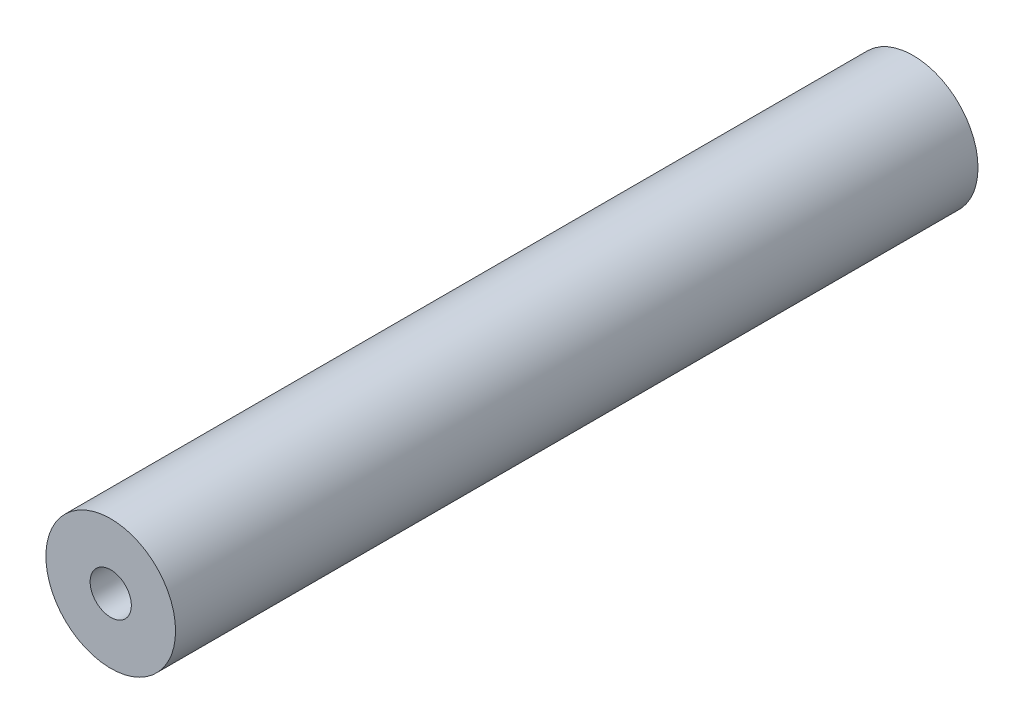
SolidWorks part; units mm, degrees
material "6061-T6 (SS)"
ref_plane "Front Plane" through (0, 0, 0) normal (0, 0, 1) x (1, 0, 0)
ref_plane "Top Plane" through (0, 0, 0) normal (0, 1, 0) x (1, 0, 0)
ref_plane "Right Plane" through (0, 0, 0) normal (1, 0, 0) x (0, 0, -1)
sketch "Sketch1" plane through (0, 0, 0) normal (0, 0, 1) x (1, 0, 0)
  circle A1 centre (0, 0) radius 6.35
  dimension "D2" = 12.7
extrude "Boss-Extrude1" add sketch "Sketch1" along normal mid plane 78.5812
hole_wizard "#10-32 Tapped Hole1" positions "3DSketch1" profile "Sketch2" tap size "#10-32" standard "ANSI Inch"
sketch3d "3DSketch1"
  line L0 (0, 0, 39.2906) -> (0, 0, -39.2906) construction
  point P0 (0, 0, -39.2906)
  point P4 (0, 0, 39.2906)
sketch "Sketch2" plane through (0, 0, -39.2906) normal (1, 0, 0) x (0, 1, 0)
  line L0 (0, 0) -> (0, 13.2428)
  line L1 (0, 13.2428) -> (2.0193, 12.0294)
  line L2 (2.0193, 12.0294) -> (2.0193, 0)
  line L5 (2.0193, 0) -> (0, 0)
  line L10 (0, 13.2428) -> (-2.0193, 12.0294) construction
  line L11 (0, -6.35) -> (0, 107.95) construction
  dimension "Tap Drill Dia." = 4.0386
  dimension "Tap Drill Depth" = 12.0294
  dimension "Drill Angle" = 118
cosmetic thread "Hole Thread1"
cosmetic thread "Hole Thread2"
